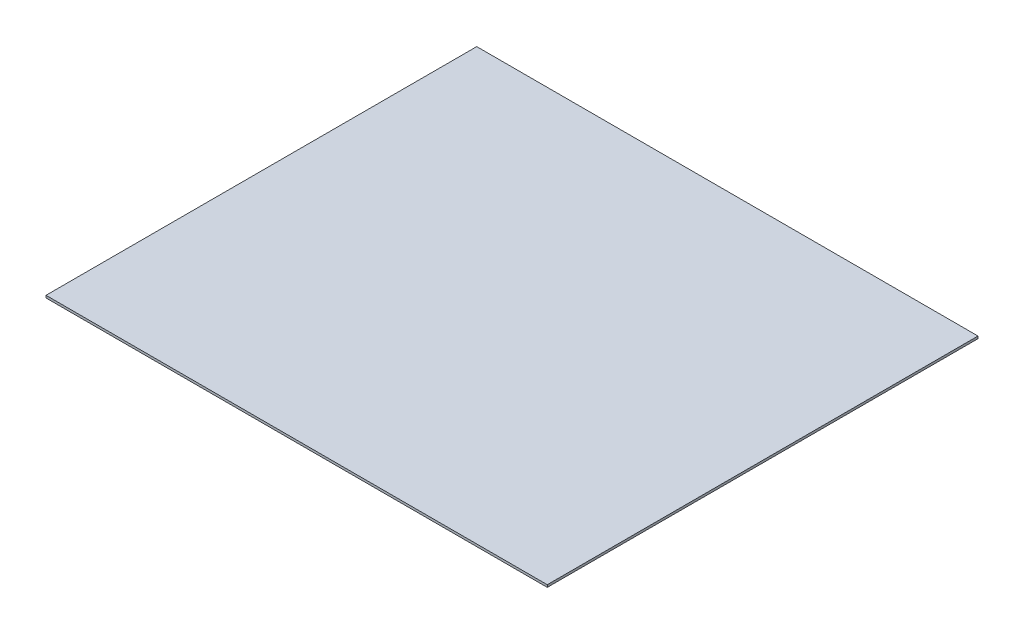
SolidWorks part; units mm, degrees
ref_plane "Alzado" through (0, 0, 0) normal (0, 0, 1) x (1, 0, 0)
ref_plane "Planta" through (0, 0, 0) normal (0, 1, 0) x (1, 0, 0)
ref_plane "Vista lateral" through (0, 0, 0) normal (1, 0, 0) x (0, 0, -1)
sketch "Croquis1" plane through (0, 0, 0) normal (0, 1, 0) x (1, 0, 0)
  line L1 (536.5, -461) -> (-536.5, -461)
  line L2 (536.5, -461) -> (536.5, 461)
  line L3 (536.5, 461) -> (-536.5, 461)
  line L4 (-536.5, -461) -> (-536.5, 461)
  line L5 (536.5, -461) -> (-536.5, 461) construction
  line L6 (536.5, 461) -> (-536.5, -461) construction
  point P0 (0, 0)
  dimension "D1" = 1073
  dimension "D2" = 922
extrude "Extruir1" add sketch "Croquis1" along normal blind 5
